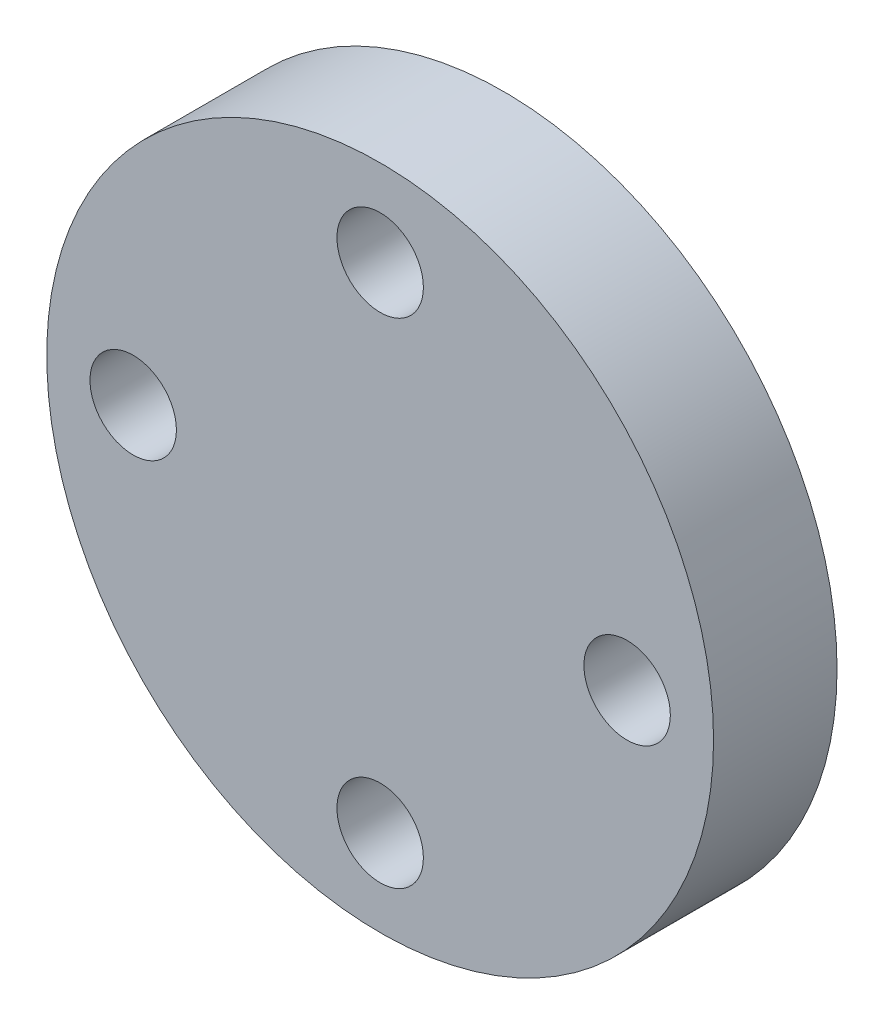
SolidWorks part; units mm, degrees
ref_plane "Front Plane" through (0, 0, 0) normal (0, 0, 1) x (1, 0, 0)
ref_plane "Top Plane" through (0, 0, 0) normal (0, 1, 0) x (1, 0, 0)
ref_plane "Right Plane" through (0, 0, 0) normal (1, 0, 0) x (0, 0, -1)
sketch "Sketch1" plane through (0, 0, 0) normal (0, 0, 1) x (1, 0, 0)
  line L0 (-10, 0) -> (0, 0) construction
  circle A0 centre (0, 0) radius 13.5
  circle A1 centre (-10, 0) radius 1.75
  circle A2 centre (0, 10) radius 1.75
  circle A3 centre (10, 0) radius 1.75
  circle A4 centre (0, -10) radius 1.75
  point P14 (0, 0)
  dimension "D1" = 27
  dimension "D3" = 3.5
  dimension "D2" = 10
  dimension "D4" = 4
extrude "Boss-Extrude1" add sketch "Sketch1" along normal blind 5
